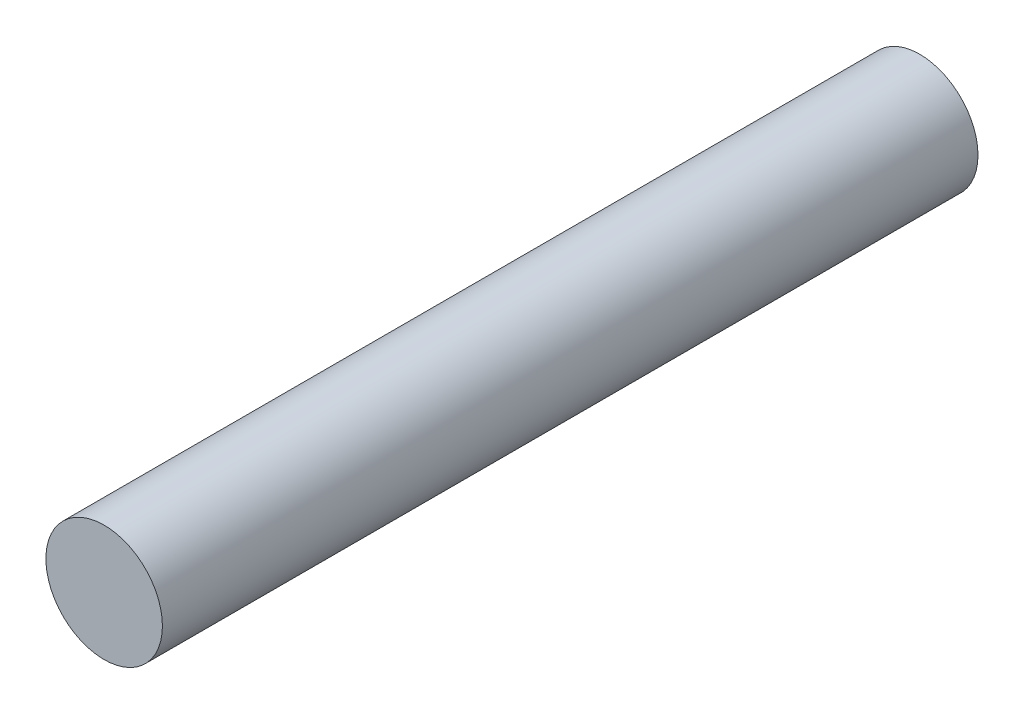
SolidWorks part; units mm, degrees
ref_plane "Front Plane" through (0, 0, 0) normal (0, 0, 1) x (1, 0, 0)
ref_plane "Top Plane" through (0, 0, 0) normal (0, 1, 0) x (1, 0, 0)
ref_plane "Right Plane" through (0, 0, 0) normal (1, 0, 0) x (0, 0, -1)
sketch "Sketch1" plane through (0, 0, 0) normal (0, 0, 1) x (1, 0, 0)
  circle A0 centre (0, 0) radius 2
  point P3 (-182.8792, -2.5787)
  dimension "D1" = 4
extrude "Boss-Extrude1" add sketch "Sketch1" along normal blind 28
